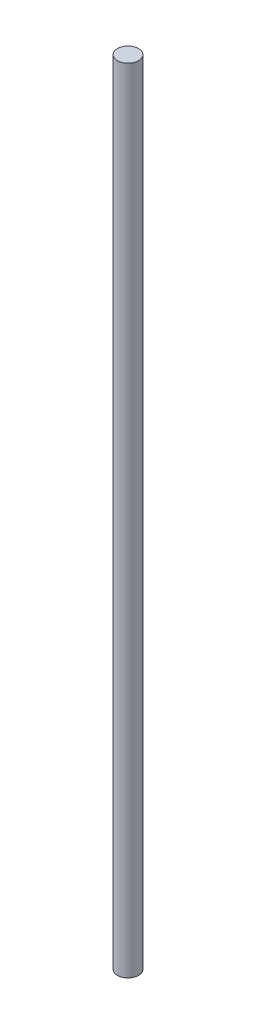
SolidWorks part; units mm, degrees
ref_plane "Front Plane" through (0, 0, 0) normal (0, 0, 1) x (1, 0, 0)
ref_plane "Top Plane" through (0, 0, 0) normal (0, 1, 0) x (1, 0, 0)
ref_plane "Right Plane" through (0, 0, 0) normal (1, 0, 0) x (0, 0, -1)
other "Configuration Table"
sketch "Sketch1" plane through (0, 0, 0) normal (0, 1, 0) x (1, 0, 0)
  circle A0 centre (150, 400) radius 8
extrude "PACK_lineer_ray_D16_1" add sketch "Sketch1" along normal blind 600 from offset 300 separate body
